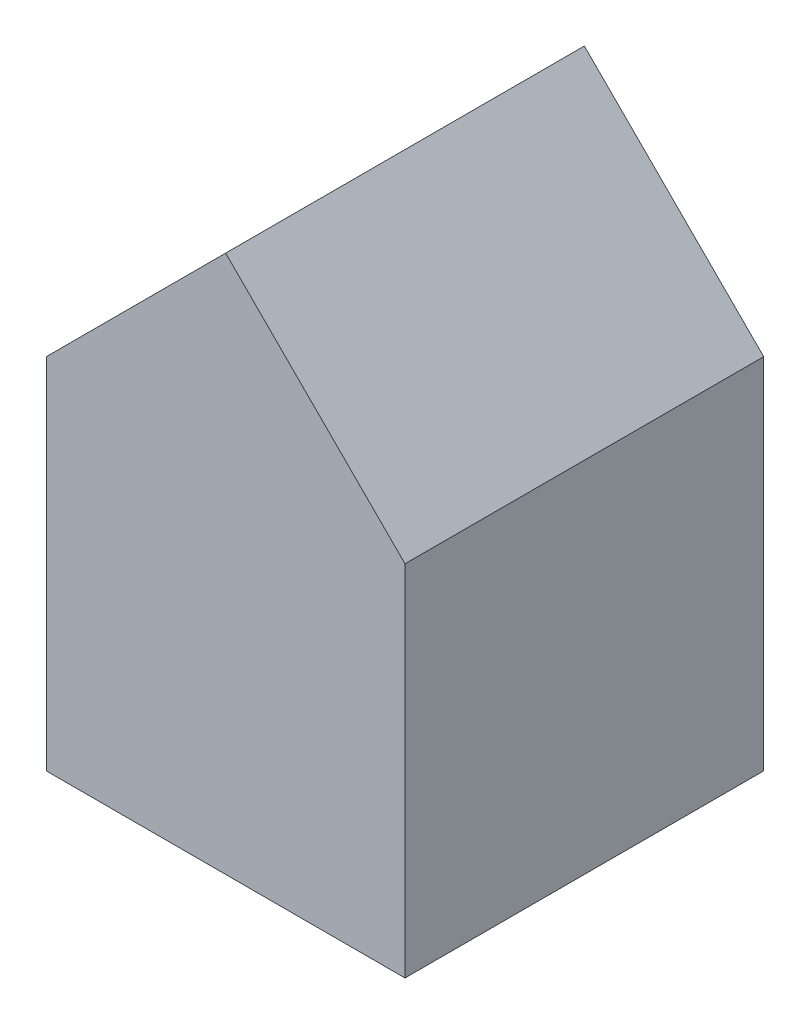
SolidWorks part; units mm, degrees
ref_plane "Front Plane" through (0, 0, 0) normal (0, 0, 1) x (1, 0, 0)
ref_plane "Top Plane" through (0, 0, 0) normal (0, 1, 0) x (1, 0, 0)
ref_plane "Right Plane" through (0, 0, 0) normal (1, 0, 0) x (0, 0, -1)
sketch "Sketch1" plane through (0, 0, 0) normal (0, 0, 1) x (1, 0, 0)
  line L0 (0, 0) -> (10, 0)
  line L1 (10, 0) -> (10, 10)
  line L2 (10, 10) -> (5, 15)
  line L3 (5, 15) -> (0, 10)
  line L4 (0, 10) -> (0, 0)
  dimension "D1" = 10
  dimension "D2" = 10
  dimension "D3" = 10
  dimension "D4" = 5
  dimension "D5" = 90
extrude "Boss-Extrude1" add sketch "Sketch1" along normal blind 10
